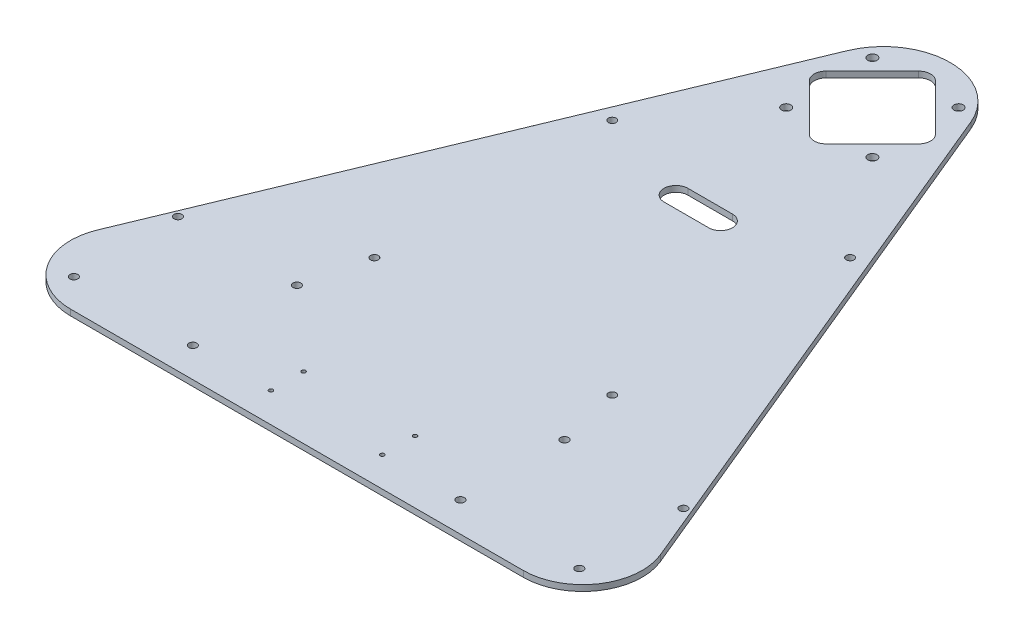
SolidWorks part; units mm, degrees
ref_plane "前视基准面" through (0, 0, 0) normal (0, 0, 1) x (1, 0, 0)
ref_plane "上视基准面" through (0, 0, 0) normal (0, 1, 0) x (1, 0, 0)
ref_plane "右视基准面" through (0, 0, 0) normal (1, 0, 0) x (0, 0, -1)
other "Configuration Table"
sketch "草图2" plane through (0, 0, 0) normal (0, 1, 0) x (1, 0, 0)
  line L0 (-41.5746, 199.6301) -> (-189.223, -156.8247)
  line L1 (-152.2678, -212.132) -> (152.2678, -212.132)
  line L2 (189.223, -156.8247) -> (41.5746, 199.6301)
  line L3 (0, 300) -> (0, -300) construction
  line L4 (-41, 175) -> (41, 175) construction
  line L5 (28.9914, 203.9914) -> (0, 175) construction
  line L6 (-36.7696, 180.6569) -> (-5.6569, 211.7696)
  line L7 (-36.7696, 169.3431) -> (-5.6569, 138.2304)
  line L8 (5.6569, 211.7696) -> (36.7696, 180.6569)
  line L9 (5.6569, 138.2304) -> (36.7696, 169.3431)
  line L10 (-42.4264, 175) -> (42.4264, 175) construction
  line L11 (0, 217.4264) -> (0, 132.5736) construction
  line L12 (-15, 57.868) -> (15, 57.868) construction
  line L13 (-170, -122.132) -> (-90, -122.132) construction
  line L14 (-170, -122.132) -> (-170, -192.132) construction
  line L15 (-170, -192.132) -> (-90, -192.132) construction
  line L16 (-90, -122.132) -> (-90, -192.132) construction
  line L17 (37.5, -170.132) -> (-37.5, -170.132) construction
  line L18 (37.5, -170.132) -> (37.5, -192.132) construction
  line L19 (37.5, -192.132) -> (-37.5, -192.132) construction
  line L20 (-37.5, -170.132) -> (-37.5, -192.132) construction
  line L21 (37.5, -170.132) -> (-37.5, -192.132) construction
  line L22 (37.5, -192.132) -> (-37.5, -170.132) construction
  line L23 (-80, 80) -> (80, 80) construction
  line L24 (-80, 80) -> (-80, -80) construction
  line L25 (-80, -80) -> (80, -80) construction
  line L26 (80, 80) -> (80, -80) construction
  line L27 (-80, 80) -> (80, -80) construction
  line L28 (-80, -80) -> (80, 80) construction
  line L29 (-15, 65.868) -> (15, 65.868)
  line L30 (-15, 49.868) -> (15, 49.868)
  circle A0 centre (0, 0) radius 300 construction
  circle A1 centre (0, 175) radius 41 construction
  circle A2 centre (28.9914, 203.9914) radius 3.1
  circle A3 centre (-28.9914, 203.9914) radius 3.1
  circle A4 centre (28.9914, 146.0086) radius 3.1
  circle A5 centre (-28.9914, 146.0086) radius 3.1
  arc A6 (36.7696, 180.6569) -> (36.7696, 169.3431) centre (31.1127, 175) cw
  arc A7 (-5.6569, 138.2304) -> (5.6569, 138.2304) centre (0, 143.8873) ccw
  arc A8 (-36.7696, 169.3431) -> (-36.7696, 180.6569) centre (-31.1127, 175) cw
  arc A9 (-5.6569, 211.7696) -> (5.6569, 211.7696) centre (0, 206.1127) cw
  arc A10 (152.2678, -212.132) -> (189.223, -156.8247) centre (152.2678, -172.132) ccw
  arc A11 (-189.223, -156.8247) -> (-152.2678, -212.132) centre (-152.2678, -172.132) ccw
  arc A12 (-41.5746, 199.6301) -> (41.5746, 199.6301) centre (0, 182.4093) cw
  circle A17 centre (-170, -122.132) radius 2.65
  circle A18 centre (-90, -122.132) radius 2.65
  circle A19 centre (-90, -192.132) radius 2.65
  circle A20 centre (-170, -192.132) radius 2.65
  circle A21 centre (90, -192.132) radius 2.65
  circle A22 centre (170, -192.132) radius 2.65
  circle A23 centre (90, -122.132) radius 2.65
  circle A24 centre (170, -122.132) radius 2.65
  circle A25 centre (37.5, -170.132) radius 1.35
  circle A26 centre (-37.5, -170.132) radius 1.35
  circle A27 centre (-37.5, -192.132) radius 1.35
  circle A28 centre (37.5, -192.132) radius 1.35
  circle A29 centre (-80, 80) radius 2.6
  circle A30 centre (80, 80) radius 2.6
  circle A31 centre (80, -80) radius 2.6
  circle A32 centre (-80, -80) radius 2.6
  arc A33 (-15, 65.868) -> (-15, 49.868) centre (-15, 57.868) ccw
  arc A34 (15, 49.868) -> (15, 65.868) centre (15, 57.868) ccw
  point P39 (212.132, -212.132)
  point P42 (-212.132, -212.132)
  point P60 (0, -181.132)
  point P79 (0, 57.868)
  dimension "D1" = 600
  dimension "D2" = 82
  dimension "D3" = 6.2
  dimension "D7" = 8
  dimension "D8" = 40
  dimension "D10" = 5.3
  dimension "D15" = 2.7
  dimension "D21" = 5.2
  dimension "D24" = 8
  dimension "D25" = 45
  dimension "D4" = 125
  dimension "D5" = 45
  dimension "D6" = 60
  dimension "D9" = 45
  dimension "D11" = 80
  dimension "D12" = 70
  dimension "D13" = 20
  dimension "D14" = 90
  dimension "D16" = 75
  dimension "D17" = 22
  dimension "D18" = 160
  dimension "D19" = 20
  dimension "D20" = 160
  dimension "D22" = 30
  dimension "D23" = 270
extrude "凸台-拉伸2" add sketch "草图2" along normal blind 4
